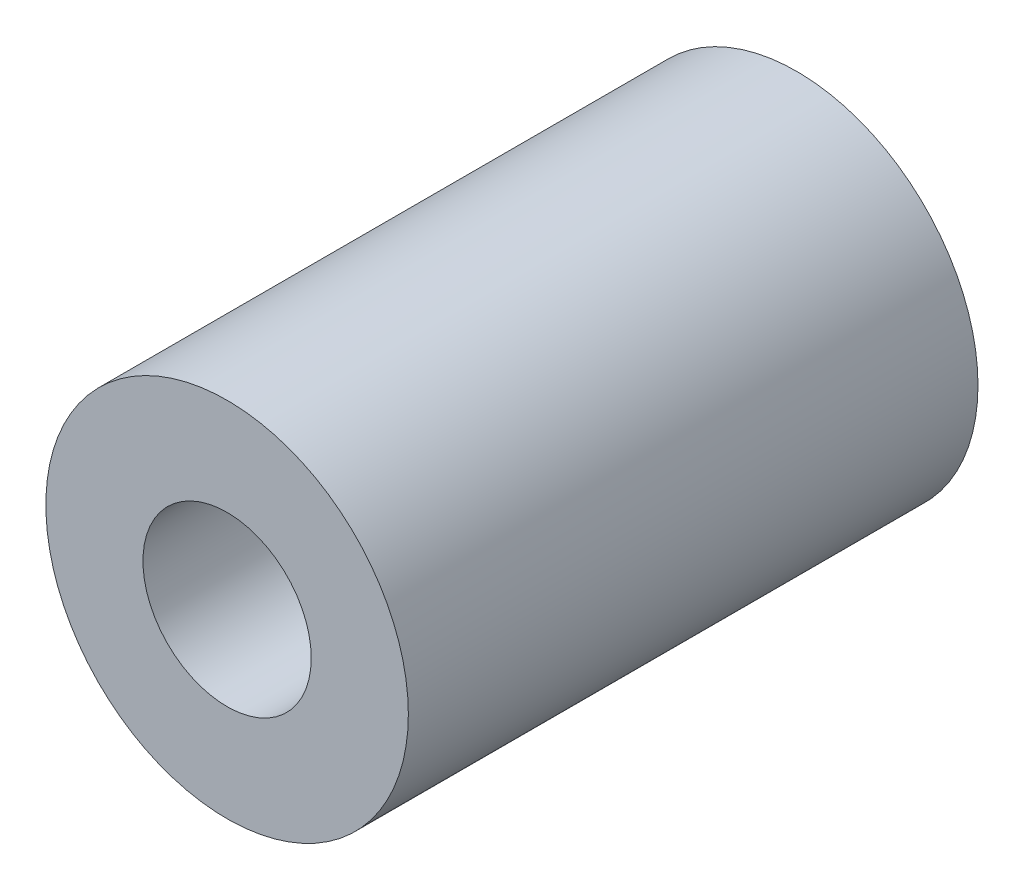
SolidWorks part; units mm, degrees
material "ABS"
ref_plane "Front Plane" through (0, 0, 0) normal (0, 0, 1) x (1, 0, 0)
ref_plane "Top Plane" through (0, 0, 0) normal (0, 1, 0) x (1, 0, 0)
ref_plane "Right Plane" through (0, 0, 0) normal (1, 0, 0) x (0, 0, -1)
sketch "Sketch1" plane through (0, 0, 0) normal (0, 0, 1) x (1, 0, 0)
  circle A0 centre (0, 0) radius 7
  dimension "D1" = 14
extrude "Boss-Extrude1" add sketch "Sketch1" along normal mid plane 22
sketch "Sketch2" plane through (0, 0, 11) normal (0, 0, 1) x (1, 0, 0)
  circle A0 centre (0, 0) radius 3.25
  dimension "D1" = 6.5
extrude "Cut-Extrude1" cut sketch "Sketch2" against normal through all both and the other way through all
